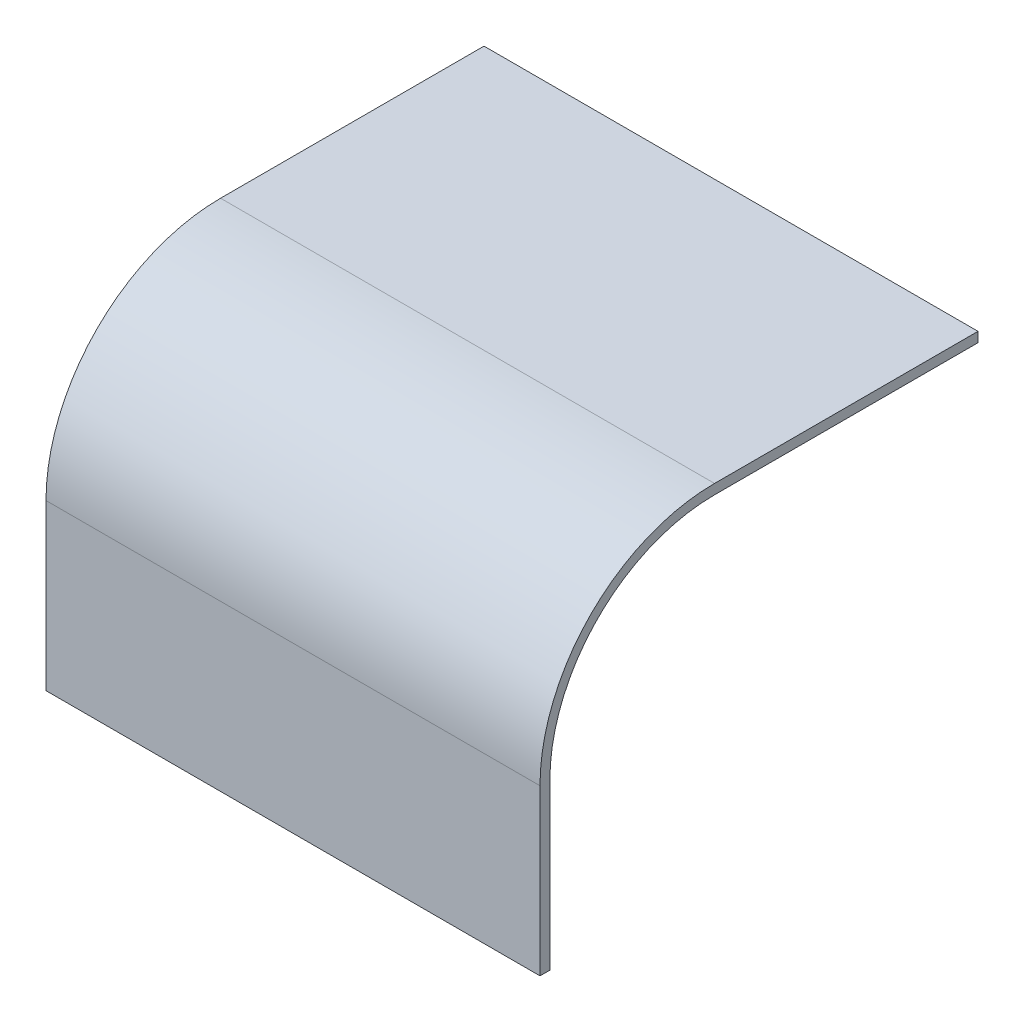
SolidWorks part; units mm, degrees
ref_plane "Alzado" through (0, 0, 0) normal (0, 0, 1) x (1, 0, 0)
ref_plane "Planta" through (0, 0, 0) normal (0, 1, 0) x (1, 0, 0)
ref_plane "Vista lateral" through (0, 0, 0) normal (1, 0, 0) x (0, 0, -1)
sketch "Croquis1" plane through (-7.3057, -32.4567, 940.9263) normal (1, 0, 0) x (0, 0, -1)
  line L0 (-80, 100) -> (0, 100) construction
  line L1 (-130, 0) -> (-130, 50) construction
  line L2 (-80, 100) -> (0, 100)
  line L3 (-130, 0) -> (-130, 50)
  line L4 (-80, 103) -> (0, 103)
  line L5 (-133, 0) -> (-133, 50)
  line L6 (0, 103) -> (0, 100)
  line L7 (-133, 0) -> (-130, 0)
  arc A0 (-80, 100) -> (-130, 50) centre (-80, 50) ccw construction
  arc A1 (-80, 100) -> (-130, 50) centre (-80, 50) ccw
  arc A2 (-80, 103) -> (-133, 50) centre (-80, 50) ccw
  dimension "D1" = 3
extrude "Saliente-Extruir1" add sketch "Croquis1" along normal mid plane 150
